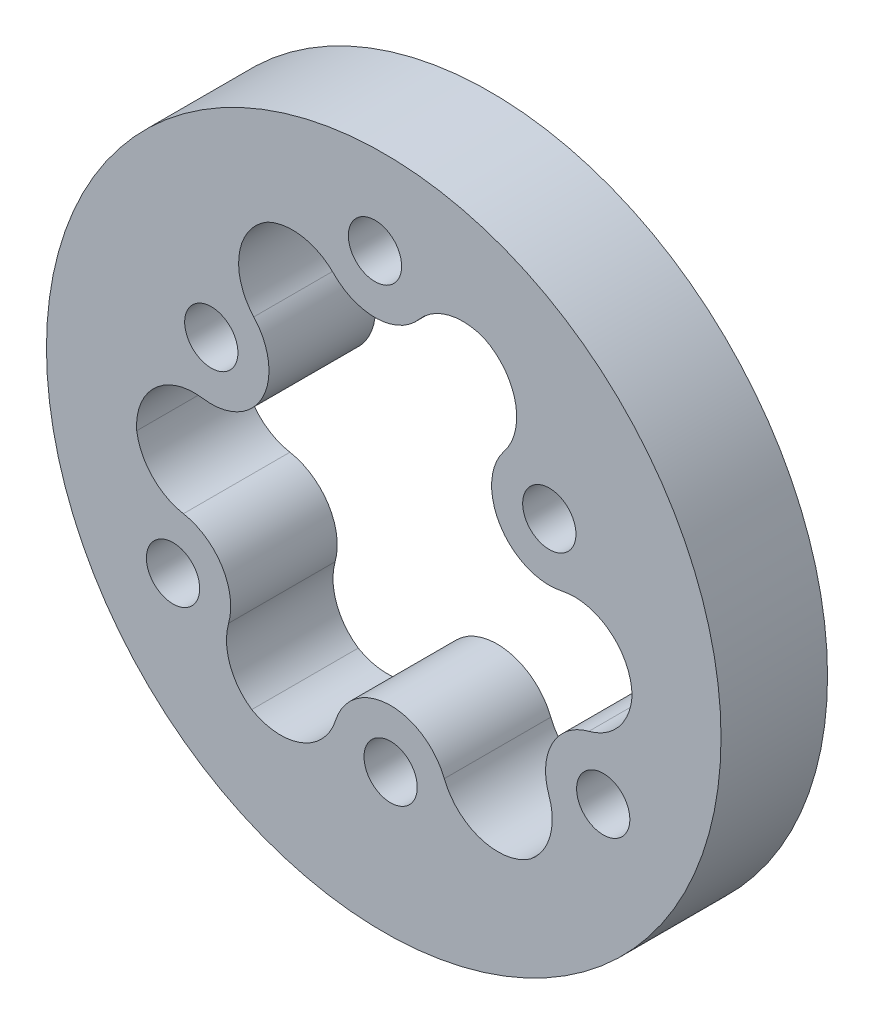
SolidWorks part; units mm, degrees
ref_plane "Plan de face" through (0, 0, 0) normal (0, 0, 1) x (1, 0, 0)
ref_plane "Plan de dessus" through (0, 0, 0) normal (0, 1, 0) x (1, 0, 0)
ref_plane "Plan de droite" through (0, 0, 0) normal (1, 0, 0) x (0, 0, -1)
sketch "Esquisse1" plane through (0, 0, 0) normal (0, 0, 1) x (1, 0, 0)
  line L0 (-0.4938, 13.9913) -> (-11.8699, -7.4233) construction
  line L1 (-11.8699, -7.4233) -> (12.3637, -6.568) construction
  line L2 (12.3637, -6.568) -> (-0.4938, 13.9913) construction
  circle A0 centre (0, 0) radius 19
  circle A2 centre (-0.4938, 13.9913) radius 1.5
  arc A12 (-2.8156, 11.7171) -> (1.9825, 11.8865) centre (-0.4938, 13.9913) ccw
  arc A16 (5.6631, 12.8003) -> (1.9825, 11.8865) centre (4.4589, 9.7817) ccw
  arc A17 (-2.8156, 11.7171) -> (-6.5514, 12.3692) centre (-5.1374, 9.443) ccw
  arc A19 (8.2538, -11.3046) -> (9.3027, -7.6602) centre (6.2417, -8.7523) ccw
  arc A20 (11.5551, -3.4202) -> (9.3027, -7.6602) centre (12.3637, -6.568) ccw
  arc A21 (11.5551, -3.4202) -> (13.9878, -0.5109) centre (10.7465, -0.2724) ccw
  circle A22 centre (12.3637, -6.568) radius 1.5
  arc A23 (-13.917, -1.4958) -> (-11.2853, -4.2263) centre (-10.7006, -1.0293) ccw
  arc A24 (-8.7395, -8.2969) -> (-11.2853, -4.2263) centre (-11.8699, -7.4233) ccw
  arc A25 (-8.7395, -8.2969) -> (-7.4363, -11.8583) centre (-5.6092, -9.1706) ccw
  circle A26 centre (-11.8699, -7.4233) radius 1.5
  circle A29 centre (-0.4938, 13.9913) radius 3.25 construction
  circle A30 centre (-9.7143, 5.1606) radius 1.5
  arc A31 (-10.1946, 1.9463) -> (-7.3198, 7.358) centre (-9.7143, 5.1606) ccw
  arc A32 (-6.5514, 12.3692) -> (-7.3198, 7.358) centre (-4.9252, 9.5554) ccw
  arc A33 (-10.1946, 1.9463) -> (-13.917, -1.4958) centre (-10.6749, -1.2681) ccw
  arc A34 (13.9878, -0.5109) -> (10.0321, 2.6601) centre (10.7378, -0.5123) ccw
  arc A35 (6.7828, 7.8557) -> (10.0321, 2.6601) centre (9.3264, 5.8326) ccw
  arc A36 (6.7828, 7.8557) -> (5.6631, 12.8003) centre (4.2393, 9.8788) ccw
  circle A37 centre (9.3264, 5.8326) radius 1.5
  arc A38 (-7.4363, -11.8583) -> (-2.7123, -10.0181) centre (-5.8126, -9.043) ccw
  arc A39 (3.4118, -9.802) -> (-2.7123, -10.0181) centre (0.388, -10.9932) ccw
  arc A40 (3.4118, -9.802) -> (8.2538, -11.3046) centre (6.4356, -8.6107) ccw
  circle A41 centre (0.388, -10.9932) radius 1.5
  circle A42 centre (-9.7143, 5.1606) radius 3.25 construction
  point P31 (0, 0)
  point P57 (0, 0)
  dimension "D1" = 38
  dimension "D2" = 3
  dimension "D3" = 3
  dimension "D4" = 6.5
  dimension "D5" = 3
  dimension "D8" = 11
  dimension "D9" = 12.7671
  dimension "D10" = 14
  dimension "D11" = 12.7671
  dimension "D12" = 3.25
  dimension "D13" = 3.25
  dimension "D14" = 6.5
  dimension "D16" = 3
  dimension "D6" = 60
  dimension "D7" = 60
extrude "Boss.-Extru.2" add sketch "Esquisse1" along normal blind 6
